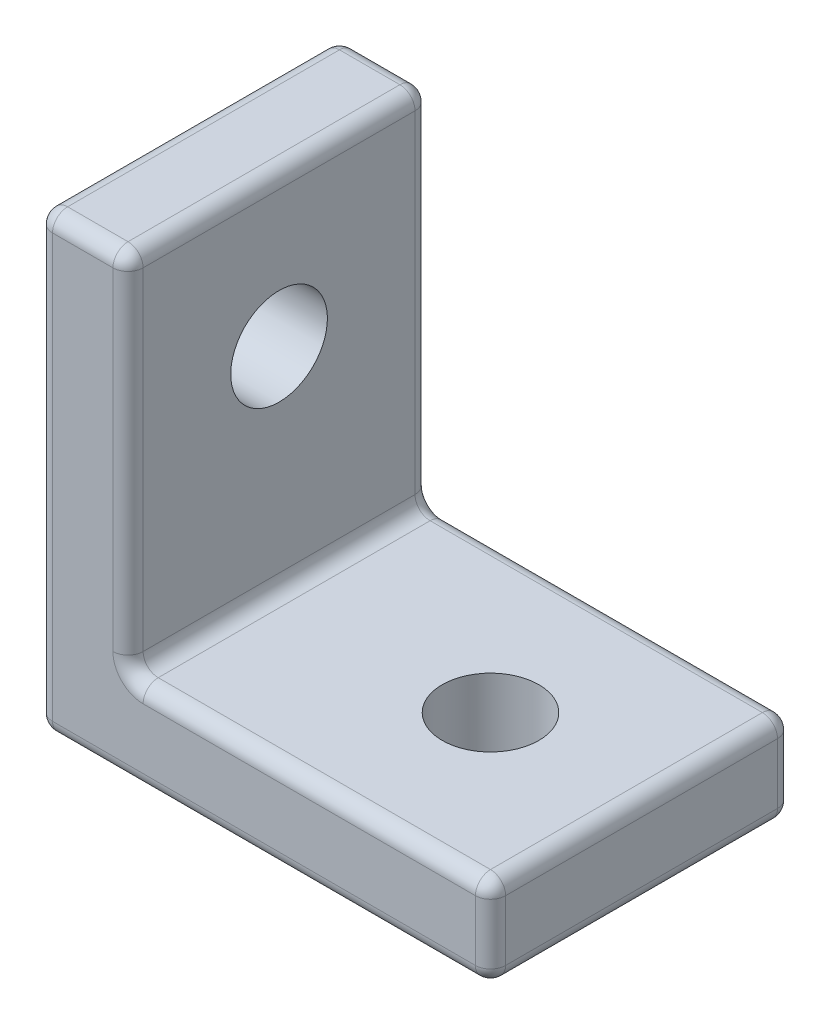
SolidWorks part; units mm, degrees
material "6061 合金"
ref_plane "Front Plane" through (0, 0, 0) normal (0, 0, 1) x (1, 0, 0)
ref_plane "Top Plane" through (0, 0, 0) normal (0, 1, 0) x (1, 0, 0)
ref_plane "Right Plane" through (0, 0, 0) normal (1, 0, 0) x (0, 0, -1)
other "Configuration Table"
sketch "草图1" plane through (0, 0, 0) normal (0, 0, 1) x (1, 0, 0)
  line L0 (0, 15) -> (0, 0)
  line L1 (0, 0) -> (15, 0)
  line L2 (15, 0) -> (15, 3)
  line L3 (15, 3) -> (3, 3)
  line L4 (3, 3) -> (3, 15)
  line L5 (3, 15) -> (0, 15)
  dimension "D1" = 3
  dimension "D2" = 3
  dimension "D3" = 15
  dimension "D4" = 15
extrude "凸台-拉伸1" add sketch "草图1" along normal blind 10
sketch "草图2" plane through (0, 0, 0) normal (-1, 0, 0) x (0, 0, 1)
  line L0 (10, 15) -> (0, 15) construction
  line L1 (0, 15) -> (0, 0) construction
  circle A0 centre (5, 10) radius 1.6
  dimension "D1" = 5
  dimension "D3" = 3.2
  dimension "D2" = 5
sketch "草图3" plane through (0, 0, 0) normal (0, -1, 0) x (1, 0, 0)
  line L0 (0, 10) -> (15, 10) construction
  line L1 (0, 6.6) -> (0, 3.4) construction
  circle A0 centre (10, 5) radius 1.6
  dimension "D1" = 5
  dimension "D3" = 3.2
  dimension "D2" = 10
extrude "切除-拉伸1" cut sketch "草图3" against normal blind 5
extrude "切除-拉伸2" cut sketch "草图2" against normal blind 5
fillet "圆角1" radius 0.5 18 edges at (1.5, 15, 0) (0, 7.5, 0) (7.5, 0, 0) (15, 1.5, 0) (9, 3, 0) (3, 9, 0) (1.5, 15, 10) (0, 7.5, 10) (7.5, 0, 10) (15, 1.5, 10) (9, 3, 10) (3, 9, 10) (15, 3, 5) (15, 0, 5) (0, 0, 5) (0, 15, 5) (3, 15, 5) (3, 3, 5)
thread "螺纹线1" pitch 0.45 start angle 0, offset 0, length 10, pitch 0.45, diameter 3.2
ref_plane "基准面1" through (5.9, 3, 5) normal (0, 0, 1) x (-1, 0, 0)
sketch "螺纹线轮廓1" plane through (5.9, 3, 5) normal (0, 0, 1) x (-1, 0, 0)
  line L0 (0, 0) -> (0, 0.45) construction
  line L1 (0, 0) -> (0.2436, 0.1406)
  line L2 (0.2436, 0.1406) -> (0.2436, 0.1969)
  line L3 (0.2436, 0.1969) -> (0, 0.3375)
  line L4 (0.2436, 0.1687) -> (0, 0.1687) construction
  line L11 (0, 0) -> (0, 0.3375)
  point P2 (0, 0)
  dimension "Pitch" = 0.45
  dimension "Profile_Angle" = 60
  dimension "Profile_Land" = 0.0562
  dimension "Profile_Height" = 0.2436
thread "螺纹线2" pitch 0.45 start angle 0, offset 0, length 10, pitch 0.45, diameter 3.2
ref_plane "基准面2" through (3, 7.5, 6.6) normal (0, -1, 0) x (0, 0, 1)
sketch "螺纹线轮廓2" plane through (3, 7.5, 6.6) normal (0, -1, 0) x (0, 0, 1)
  line L0 (0, 0) -> (0, 0.45) construction
  line L1 (0, 0) -> (0.2436, 0.1406)
  line L2 (0.2436, 0.1406) -> (0.2436, 0.1969)
  line L3 (0.2436, 0.1969) -> (0, 0.3375)
  line L4 (0.2436, 0.1687) -> (0, 0.1687) construction
  line L11 (0, 0) -> (0, 0.3375)
  point P2 (0, 0)
  dimension "Pitch" = 0.45
  dimension "Profile_Angle" = 60
  dimension "Profile_Land" = 0.0562
  dimension "Profile_Height" = 0.2436
